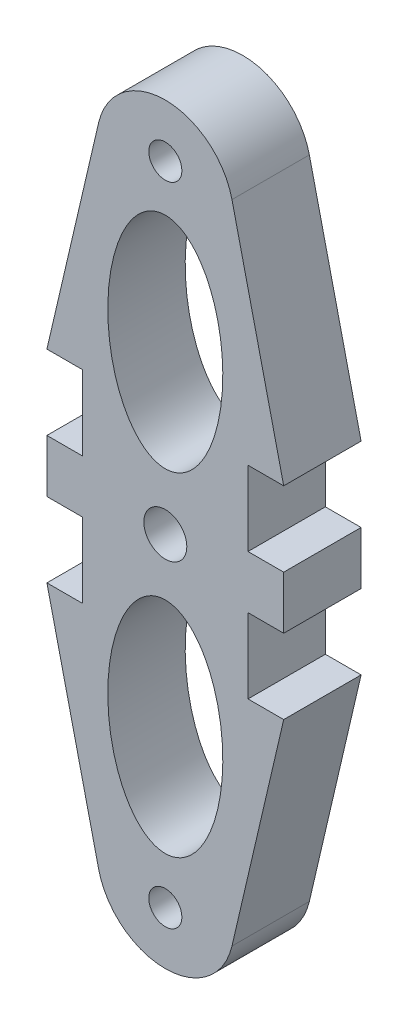
SolidWorks part; units mm, degrees
material "Acrylic (Medium-high impact)"
ref_plane "Front Plane" through (0, 0, 0) normal (0, 0, 1) x (1, 0, 0)
ref_plane "Top Plane" through (0, 0, 0) normal (0, 1, 0) x (1, 0, 0)
ref_plane "Right Plane" through (0, 0, 0) normal (1, 0, 0) x (0, 0, -1)
sketch "Sketch1" plane through (0, 0, 0) normal (0, 0, 1) x (1, 0, 0)
  line L0 (-213.0435, 465.4025) -> (49786.9565, 465.4025) construction
  line L1 (781.4092, 465.4025) -> (778.7092, 465.4025)
  line L2 (781.4092, 465.4025) -> (781.4092, 471.0525)
  line L3 (781.4092, 471.0525) -> (778.7092, 471.0525)
  line L4 (787.6592, -515.9253) -> (787.6592, 49484.0747) construction
  line L5 (-215.2235, 463.4024) -> (49784.7765, 463.4024) construction
  line L6 (793.9092, 471.0525) -> (793.9092, 487.8374) construction
  line L7 (-217.5077, 461.4022) -> (49782.4923, 461.4022) construction
  line L8 (785.6592, -537.0976) -> (785.6592, 49462.9024) construction
  line L9 (789.6592, -536.5976) -> (789.6592, 49463.4024) construction
  line L10 (793.9092, 465.4025) -> (796.6092, 465.4025)
  line L11 (781.4092, 471.0525) -> (793.9092, 471.0525) construction
  line L12 (793.9092, 471.0525) -> (796.6092, 471.0525)
  line L13 (793.9092, 465.4025) -> (793.9092, 471.0525)
  line L14 (778.7092, 465.4025) -> (778.7092, 461.4022)
  line L15 (796.6092, 465.4025) -> (796.6092, 461.4022)
  line L16 (786.4092, 487.8374) -> (782.6202, 487.8374) construction
  line L17 (781.4092, 461.4022) -> (778.7092, 461.4022)
  line L19 (781.4092, 455.7522) -> (778.7092, 455.7522)
  line L20 (781.4092, 461.4022) -> (781.4092, 455.7522)
  line L21 (793.9092, 461.4022) -> (796.6092, 461.4022)
  line L22 (793.9092, 461.4022) -> (793.9092, 455.7522)
  line L23 (793.9092, 455.7522) -> (796.6092, 455.7522)
  line L24 (778.7092, 471.0525) -> (782.6202, 487.8374)
  line L25 (792.6982, 487.8374) -> (796.6092, 471.0525)
  line L26 (792.6982, 438.9674) -> (796.6092, 455.7522)
  line L27 (788.9092, 438.9674) -> (792.6982, 438.9674) construction
  line L28 (786.4092, 438.9674) -> (782.6202, 438.9674) construction
  line L29 (778.7092, 455.7522) -> (782.6202, 438.9674)
  line L35 (788.9092, 487.8374) -> (792.6982, 487.8374) construction
  arc A0 (782.6202, 487.8374) -> (792.6982, 487.8374) centre (787.6592, 486.6632) cw
  arc A1 (782.6202, 438.9674) -> (792.6982, 438.9674) centre (787.6592, 440.1415) ccw
  circle A3 centre (787.6592, 487.8374) radius 1.25
  circle A5 centre (787.6592, 438.9674) radius 1.25
  circle A6 centre (787.6592, 463.4024) radius 1.625
  ellipse E0 centre (787.6592, 475.9983) end of major axis (787.6592, 467.6962) minor radius 4.3465
  ellipse E1 centre (787.6592, 450.8064) end of major axis (787.6592, 442.5043) minor radius 4.3465
  point P10 (778.7092, 463.4024)
  point P19 (796.6092, 463.4024)
  dimension "D3" = 5.65
  dimension "D10" = 5.174
  dimension "D2" = 2.7
  dimension "D4" = 24.435
  dimension "D5" = 12.5
  dimension "D6" = 16.6042
  dimension "D7" = 8.693
  dimension "D8" = 2.2937
extrude "Boss-Extrude1" add sketch "Sketch1" along normal blind 5.85
